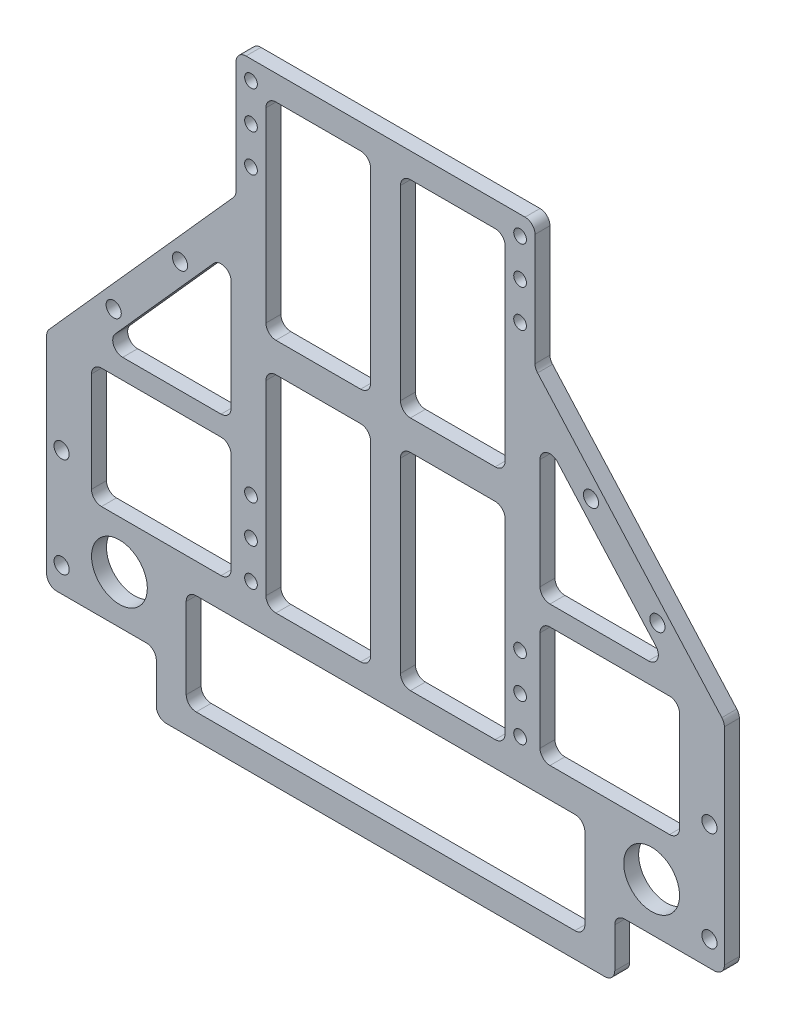
SolidWorks part; units mm, degrees
material "Thornel Mat VMA"
ref_plane "前视基准面" through (0, 0, 0) normal (0, 0, 1) x (1, 0, 0)
ref_plane "上视基准面" through (0, 0, 0) normal (0, 1, 0) x (1, 0, 0)
ref_plane "右视基准面" through (0, 0, 0) normal (1, 0, 0) x (0, 0, -1)
other "Configuration Table"
sketch "草图1" plane through (0, 0, 0) normal (0, 0, 1) x (1, 0, 0)
  line L1 (-30, -62) -> (30, -62)
  line L2 (-30, -62) -> (-30, 62)
  line L3 (-30, 62) -> (30, 62)
  line L4 (30, -62) -> (30, 62)
  line L5 (-30, -62) -> (30, 62) construction
  line L6 (-30, 62) -> (30, -62) construction
  point P0 (0, 0)
  dimension "D1" = 124
  dimension "D2" = 60
extrude "凸台-拉伸1" add sketch "草图1" along normal blind 3
sketch "草图2" plane through (0, 0, 0) normal (0, 0, -1) x (-1, 0, 0)
  line L0 (-20.5964, 51.032) -> (-67.025, -0.968) construction
  line L1 (20.5964, 51.032) -> (67.025, -0.968) construction
  line L2 (-30, 40.5) -> (-67.025, -0.968) construction
  line L3 (30, 40.5) -> (67.025, -0.968) construction
  line L4 (-66.6485, -4.3) -> (66.6485, -4.3)
  line L5 (-30, 40.5) -> (30, 40.5) construction
  line L6 (-30, -62) -> (-30, 62) construction
  line L7 (30, 62) -> (30, -62) construction
  line L8 (66.6485, -4.3) -> (30, 36.7463)
  line L9 (30, 36.7463) -> (-30, 36.7463)
  line L10 (-30, 36.7463) -> (-66.6485, -4.3)
  dimension "D1" = 5
  dimension "D2" = 5
  dimension "D3" = 4.3
extrude "凸台-拉伸2" add sketch "草图2" against normal up to surface (3 mm away) up to face at (0, 0, 3)
sketch "草图3" plane through (0, 0, 3) normal (0, 0, 1) x (1, 0, 0)
  line L0 (-68, -4.3) -> (-68, -62)
  line L1 (-66.6485, -4.3) -> (-30, -4.3) construction
  line L2 (-68, -62) -> (68, -62)
  line L3 (68, -62) -> (68, -4.3)
  line L4 (30, -4.3) -> (66.6485, -4.3) construction
  line L5 (-68, -4.3) -> (68, -4.3)
  line L6 (0, 0) -> (0, -4.3) construction
  line L7 (-30, -62) -> (30, -62) construction
  dimension "D1" = 136
extrude "凸台-拉伸3" add sketch "草图3" against normal up to surface (3 mm away) up to face at (0, 5.6292, 0)
sketch "草图4" plane through (0, 0, 3) normal (0, 0, 1) x (1, 0, 0)
  line L0 (68, -4.3) -> (68, -5.8137)
  line L2 (68, -5.8137) -> (66.6485, -4.3)
  line L3 (66.6485, -4.3) -> (68, -4.3)
  line L4 (0, 0) -> (0, -62) construction
  line L5 (-68, -62) -> (68, -62) construction
  line L6 (-66.6485, -4.3) -> (-68, -4.3)
  line L7 (-68, -5.8137) -> (-66.6485, -4.3)
  line L8 (-68, -4.3) -> (-68, -5.8137)
  line L9 (66.6485, -4.3) -> (30, 36.7463) construction
  line L10 (68, -62) -> (68, -4.3) construction
extrude "切除-拉伸1" cut sketch "草图4" against normal up to surface (3 mm away) up to face at (0, 5.6292, 0)
sketch "草图5" plane through (0, 0, 0) normal (0, 0, -1) x (-1, 0, 0)
  line L5 (-68, -62) -> (-46, -62)
  line L6 (-68, -62) -> (-68, -50)
  line L7 (-68, -50) -> (-46, -50)
  line L8 (-46, -62) -> (-46, -50)
  dimension "D1" = 22
  dimension "D2" = 12
extrude "切除-拉伸2" cut sketch "草图5" against normal blind 10
mirror "镜向1" about plane through (0, 0, 0) normal (1, 0, 0) of "切除-拉伸2"
sketch "草图6" plane through (0, 0, 0) normal (0, 0, -1) x (-1, 0, 0)
  circle A0 centre (27, -21.3) radius 1.35 construction
  circle A1 centre (-27, -21.3) radius 1.35 construction
  circle A2 centre (27, 50.7) radius 1.35 construction
  circle A3 centre (-27, 50.7) radius 1.35 construction
  circle A4 centre (27, -21.3) radius 1.35 construction
  circle A5 centre (-27, -21.3) radius 1.35 construction
  circle A6 centre (27, 50.7) radius 1.35 construction
  circle A7 centre (-27, 50.7) radius 1.35 construction
  circle A8 centre (-27, 50.7) radius 1.275
  circle A9 centre (27, 50.7) radius 1.275
  circle A10 centre (27, -21.3) radius 1.275
  circle A11 centre (-27, -21.3) radius 1.275
  dimension "D1" = 2.55
extrude "切除-拉伸3" cut sketch "草图6" against normal blind 10
pattern_linear "阵列(线性)1" count 2 spacing 7.5 along (0, 1, 0) of "切除-拉伸3"
pattern_linear "阵列(线性)2" count 2 spacing 7.5 along (0, -1, 0) of "切除-拉伸3"
sketch "草图7" plane through (0, 0, 0) normal (0, 0, -1) x (-1, 0, 0)
  circle A0 centre (54.5544, 4.741) radius 1.25 construction
  circle A1 centre (41.2341, 19.6597) radius 1.25 construction
  circle A2 centre (65, -25) radius 1.25 construction
  circle A3 centre (65, -45) radius 1.25 construction
  circle A4 centre (54.5544, 4.741) radius 1.25 construction
  circle A5 centre (41.2341, 19.6597) radius 1.25 construction
  circle A6 centre (65, -25) radius 1.25 construction
  circle A7 centre (65, -45) radius 1.25 construction
  circle A8 centre (65, -45) radius 1.525
  circle A9 centre (65, -25) radius 1.525
  circle A10 centre (41.2341, 19.6597) radius 1.525
  circle A11 centre (54.5544, 4.741) radius 1.525
  dimension "D1" = 3.05
extrude "切除-拉伸4" cut sketch "草图7" against normal blind 10
mirror "镜向2" about plane through (0, 0, 0) normal (1, 0, 0) of "切除-拉伸4"
fillet "圆角1" radius 2 12 edges at (-68, -50, 1.5) (-68, -5.8137, 1.5) (-30, 36.7463, 1.5) (-30, 62, 1.5) (30, 62, 1.5) (30, 36.7463, 1.5) (68, -5.8137, 1.5) (68, -50, 1.5) (46, -50, 1.5) (46, -62, 1.5) (-46, -62, 1.5) (-46, -50, 1.5)
sketch "草图8" plane through (0, 0, 0) normal (0, 0, -1) x (-1, 0, 0)
  line L0 (-28, 62) -> (28, 62) construction
  line L1 (-24, 57) -> (24, 57)
  line L2 (-24, 57) -> (-24, -31.8)
  line L3 (-24, -31.8) -> (24, -31.8)
  line L4 (24, 57) -> (24, -31.8)
  line L5 (0, 57) -> (0, -31.8) construction
  line L6 (-24, 12.6) -> (24, 12.6) construction
  line L7 (-24, 9.6) -> (24, 9.6)
  line L8 (-3, 57) -> (-3, -31.8)
  line L9 (-24, 15.6) -> (24, 15.6)
  line L10 (3, 57) -> (3, -31.8)
  circle A0 centre (27, 43.2) radius 1.275 construction
  circle A1 centre (-27, 43.2) radius 1.275 construction
  circle A2 centre (27, -28.8) radius 1.275 construction
  arc A3 (-24, 9.6) -> (-24, 15.6) centre (-24, 12.6) cw
  arc A4 (24, 9.6) -> (24, 15.6) centre (24, 12.6) ccw
  arc A5 (-3, 57) -> (3, 57) centre (0, 57) cw
  arc A6 (-3, -31.8) -> (3, -31.8) centre (0, -31.8) ccw
  dimension "D1" = 5
  dimension "D2" = 3
  dimension "D3" = 3
  dimension "D4" = 3
  dimension "D5" = 3
  dimension "D6" = 3
extrude "切除-拉伸5" cut sketch "草图8" against normal blind 22 contours L8 L7 L2 L3 | L7 L10 L3 L4 | L1 L10 L9 L4 | L2 L9 L8 L1
fillet "圆角2" radius 2 16 edges at (-24, 57, 1.5) (-24, 15.6, 1.5) (-3, 15.6, 1.5) (-3, 57, 1.5) (3, -31.8, 1.5) (24, -31.8, 1.5) (24, 9.6, 1.5) (3, 9.6, 1.5) (-24, -31.8, 1.5) (-3, -31.8, 1.5) (3, 57, 1.5) (3, 15.6, 1.5) (24, 15.6, 1.5) (24, 57, 1.5) (-24, 9.6, 1.5) (-3, 9.6, 1.5)
sketch "草图10" plane through (0, 0, 0) normal (0, 0, -1) x (-1, 0, 0)
  line L0 (5, -31.8) -> (22, -31.8) construction
  line L1 (-40, -57) -> (40, -57)
  line L2 (-40, -57) -> (-40, -36.8)
  line L3 (-40, -36.8) -> (40, -36.8)
  line L4 (40, -57) -> (40, -36.8)
  line L5 (-40, -57) -> (40, -36.8) construction
  line L6 (-40, -36.8) -> (40, -57) construction
  line L7 (44, -62) -> (-44, -62) construction
  line L8 (46, -60) -> (46, -52) construction
  line L9 (-46, -60) -> (-46, -52) construction
  point P0 (0, -46.9)
  dimension "D1" = 5
  dimension "D2" = 5
  dimension "D3" = 6
  dimension "D4" = 6
extrude "切除-拉伸6" cut sketch "草图10" against normal up to surface (3 mm away) up to face at (13.5, 36.3, 3)
fillet "圆角3" radius 2 4 edges at (40, -57, 1.5) (40, -36.8, 1.5) (-40, -57, 1.5) (-40, -36.8, 1.5)
sketch "草图11" plane through (0, 0, 3) normal (0, 0, 1) x (1, 0, 0)
  line L0 (-31, 26.6175) -> (-59, -4.7425)
  line L1 (-59, -4.7425) -> (-59, -30.8)
  line L2 (-59, -30.8) -> (-31, -30.8)
  line L3 (-31, -30.8) -> (-31, 26.6175)
  line L4 (-24, 55) -> (-24, 17.6) construction
  line L5 (-30.5081, 36.1772) -> (-67.4919, -5.2446) construction
  line L6 (38, -36.8) -> (-38, -36.8) construction
  circle A0 centre (-65, -25) radius 1.525 construction
  dimension "D1" = 7
  dimension "D2" = 6
  dimension "D3" = 6
  dimension "D4" = 6
extrude "切除-拉伸7" cut sketch "草图11" against normal up to surface (3 mm away) up to face at (0, -46.9, 0)
mirror "镜向3" about plane through (0, 0, 0) normal (1, 0, 0) of "切除-拉伸7"
sketch "草图12" plane through (0, 0, 0) normal (0, 0, -1) x (-1, 0, 0)
  line L0 (-59, -4.7425) -> (-31, -4.7425) construction
  line L1 (-31, -30.8) -> (-31, 26.6175) construction
  line L2 (-59, -6.7425) -> (-31, -6.7425)
  line L3 (-59, -2.7425) -> (-31, -2.7425)
  arc A0 (-59, -6.7425) -> (-59, -2.7425) centre (-59, -4.7425) cw
  arc A1 (-31, -6.7425) -> (-31, -2.7425) centre (-31, -4.7425) ccw
  dimension "D1" = 2
  dimension "D2" = 2
extrude "凸台-拉伸5" add sketch "草图12" against normal up to surface (3 mm away) up to face at (-13.5, 36.3, 3)
mirror "镜向4" about plane through (0, 0, 0) normal (1, 0, 0) of "凸台-拉伸5"
sketch "草图13" plane through (0, 0, 0) normal (0, 0, -1) x (-1, 0, 0)
  line L1 (59, -30.8) -> (31, -30.8) construction
  line L3 (48, -50) -> (66, -50) construction
  line L5 (68, -6.5766) -> (68, -48) construction
  circle A0 centre (53.4, -40.4) radius 5.6
  dimension "D1" = 4
  dimension "D2" = 9
  dimension "D3" = 4
extrude "切除-拉伸8" cut sketch "草图13" against normal blind 22 and the other way through all
mirror "镜向5" about plane through (0, 0, 0) normal (1, 0, 0) of "切除-拉伸8"
fillet "圆角4" radius 2 14 edges at (31, 26.6175, 1.5) (31, -2.7425, 1.5) (57.2143, -2.7425, 1.5) (31, -6.7425, 1.5) (31, -30.8, 1.5) (-59, -6.7425, 1.5) (-59, -30.8, 1.5) (-31, -30.8, 1.5) (-31, -6.7425, 1.5) (-31, 26.6175, 1.5) (-57.2143, -2.7425, 1.5) (-31, -2.7425, 1.5) (59, -6.7425, 1.5) (59, -30.8, 1.5)
